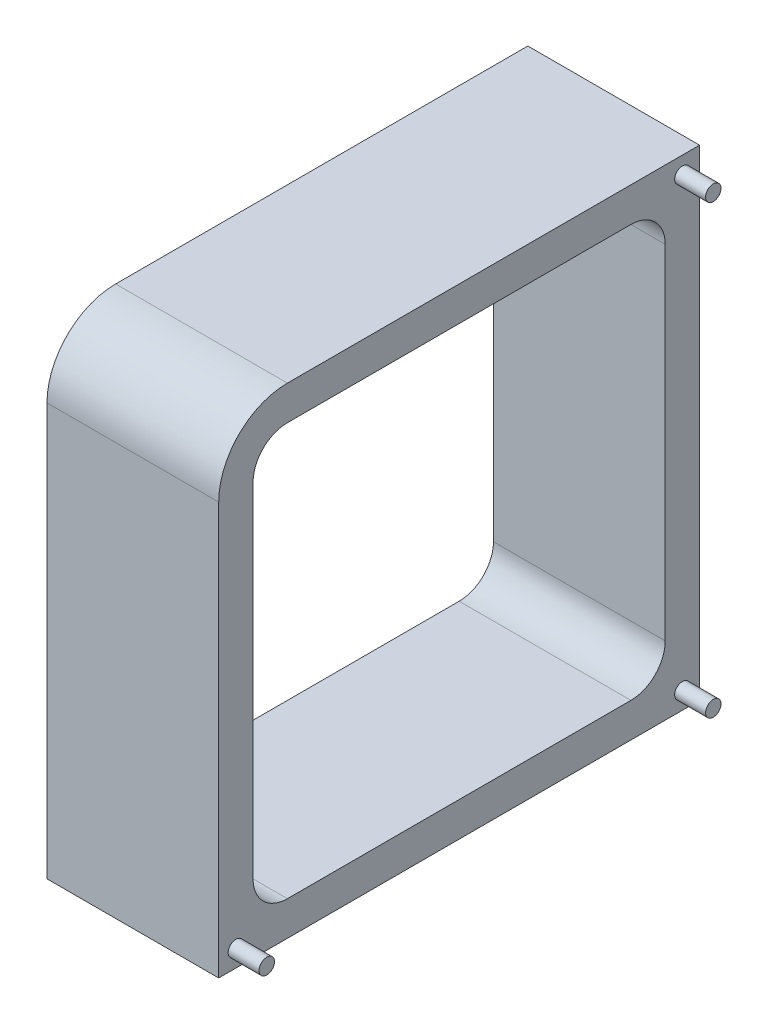
SolidWorks part; units mm, degrees
ref_plane "前视基准面" through (0, 0, 0) normal (0, 0, 1) x (1, 0, 0)
ref_plane "上视基准面" through (0, 0, 0) normal (0, 1, 0) x (1, 0, 0)
ref_plane "右视基准面" through (0, 0, 0) normal (1, 0, 0) x (0, 0, -1)
other "Configuration Table"
sketch "草图1" plane through (0, 0, 0) normal (1, 0, 0) x (0, 0, -1)
  line L1 (0, 0) -> (140, 0)
  line L2 (0, 0) -> (0, 120)
  line L3 (20, 140) -> (140, 140)
  line L4 (140, 0) -> (140, 140)
  line L5 (20, 10) -> (120, 10)
  line L6 (10, 20) -> (10, 120)
  line L7 (20, 130) -> (120, 130)
  line L8 (130, 20) -> (130, 120)
  arc A0 (130, 120) -> (120, 130) centre (120, 120) ccw
  arc A1 (120, 10) -> (130, 20) centre (120, 20) ccw
  arc A2 (10, 20) -> (20, 10) centre (20, 20) ccw
  arc A3 (10, 120) -> (20, 130) centre (20, 120) cw
  arc A4 (0, 120) -> (20, 140) centre (20, 120) cw
  point P11 (130, 130)
  point P14 (130, 10)
  point P17 (10, 10)
  dimension "D7" = 10
  dimension "D8" = 20
  dimension "D1" = 140
  dimension "D2" = 140
  dimension "D3" = 120
  dimension "D4" = 120
  dimension "D5" = 10
  dimension "D6" = 10
extrude "凸台-拉伸1" add sketch "草图1" along normal blind 50
sketch "草图2" plane through (50, 0, 0) normal (1, 0, 0) x (0, 0, -1)
  line L1 (0, 0) -> (140, 0) construction
  line L2 (0, 120) -> (0, 0) construction
  line L3 (140, 0) -> (140, 140) construction
  line L4 (140, 140) -> (20, 140) construction
  circle A0 centre (5, 5) radius 2.25
  circle A1 centre (135, 5) radius 2.25
  circle A2 centre (135, 135) radius 2.25
  point P8 (0, 0)
  point P10 (7.8398, 1.8381)
  dimension "D1" = 4.5
  dimension "D2" = 4.5
  dimension "D3" = 4.5
  dimension "D4" = 5
  dimension "D5" = 5
  dimension "D6" = 5
  dimension "D7" = 5
  dimension "D8" = 5
  dimension "D9" = 5
extrude "凸台-拉伸2" add sketch "草图2" along normal blind 9
